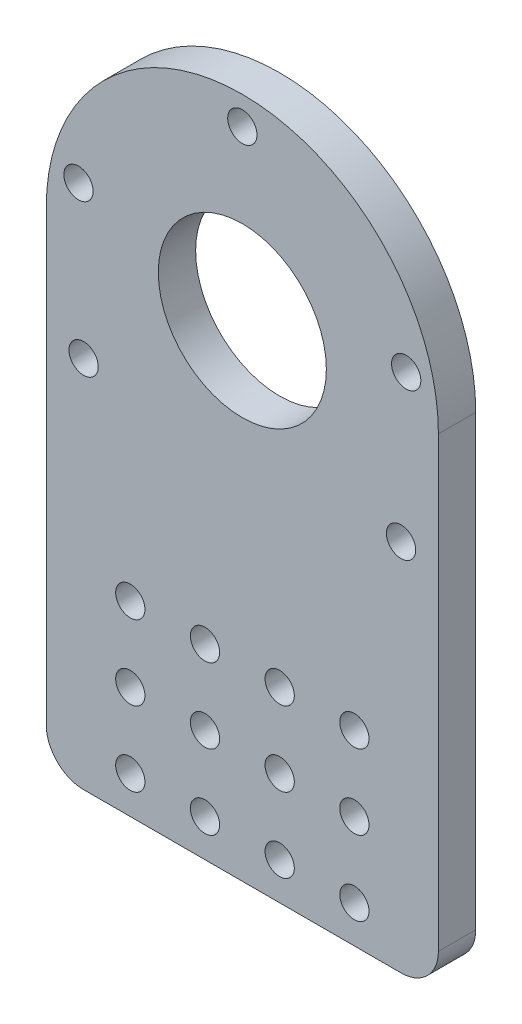
SolidWorks part; units mm, degrees
ref_plane "Front Plane" through (0, 0, 0) normal (0, 0, 1) x (1, 0, 0)
ref_plane "Top Plane" through (0, 0, 0) normal (0, 1, 0) x (1, 0, 0)
ref_plane "Right Plane" through (0, 0, 0) normal (1, 0, 0) x (0, 0, -1)
sketch "Sketch1" plane through (0, 0, 0) normal (0, 0, 1) x (1, 0, 0)
  line L0 (33.3375, 0) -> (33.3375, -82.55)
  line L3 (-33.3375, 0) -> (-33.3375, -82.55)
  line L5 (-33.3375, -82.55) -> (33.3375, -82.55)
  line L6 (-6.35, -63.5) -> (6.35, -63.5) construction
  line L7 (0, 0) -> (0, -82.55) construction
  circle A0 centre (0, 0) radius 20.6375 construction
  arc A1 (33.3375, 0) -> (-33.3375, 0) centre (0, 0) ccw
  circle A2 centre (0, 0) radius 33.3375 construction
  circle A3 centre (0, 0) radius 14.2875
  circle A4 centre (-19.05, -76.2) radius 2.4892
  circle A5 centre (-6.35, -76.2) radius 2.4892
  circle A6 centre (-6.35, -63.5) radius 2.4892
  circle A7 centre (-19.05, -63.5) radius 2.4892
  circle A8 centre (6.35, -76.2) radius 2.4892
  circle A9 centre (6.35, -63.5) radius 2.4892
  circle A10 centre (-19.05, -50.8) radius 2.4892
  circle A11 centre (-6.35, -50.8) radius 2.4892
  circle A12 centre (6.35, -50.8) radius 2.4892
  circle A13 centre (26.9875, -19.05) radius 2.4892
  circle A14 centre (19.05, -76.2) radius 2.4892
  circle A16 centre (19.05, -63.5) radius 2.4892
  circle A18 centre (19.05, -50.8) radius 2.4892
  circle A20 centre (0, 28.575) radius 2.4892
  circle A21 centre (-27.8605, 6.35) radius 2.4892
  circle A22 centre (27.8605, 6.35) radius 2.4892
  circle A23 centre (0, 0) radius 28.575 construction
  circle A24 centre (-26.9875, -19.05) radius 2.4892
  point P0 (0, 0)
  point P29 (0, -63.5)
  dimension "D2" = 41.275
  dimension "D4" = 28.575
  dimension "D6" = 4.9784
  dimension "D5" = 4.9784
  dimension "D1" = 12.7
  dimension "D3" = 82.55
  dimension "D7" = 6.35
  dimension "D10" = 12.7
  dimension "D11" = 12.7
  dimension "D12" = 6.35
  dimension "D13" = 19.05
  dimension "D14" = 28.575
  dimension "D15" = 6.35
  dimension "D8" = 4
  dimension "D9" = 3
extrude "Boss-Extrude1" add sketch "Sketch1" along normal mid plane 6.35
fillet "Fillet1" radius 6.35 2 edges at (-33.3375, -82.55, 0) (33.3375, -82.55, 0)
